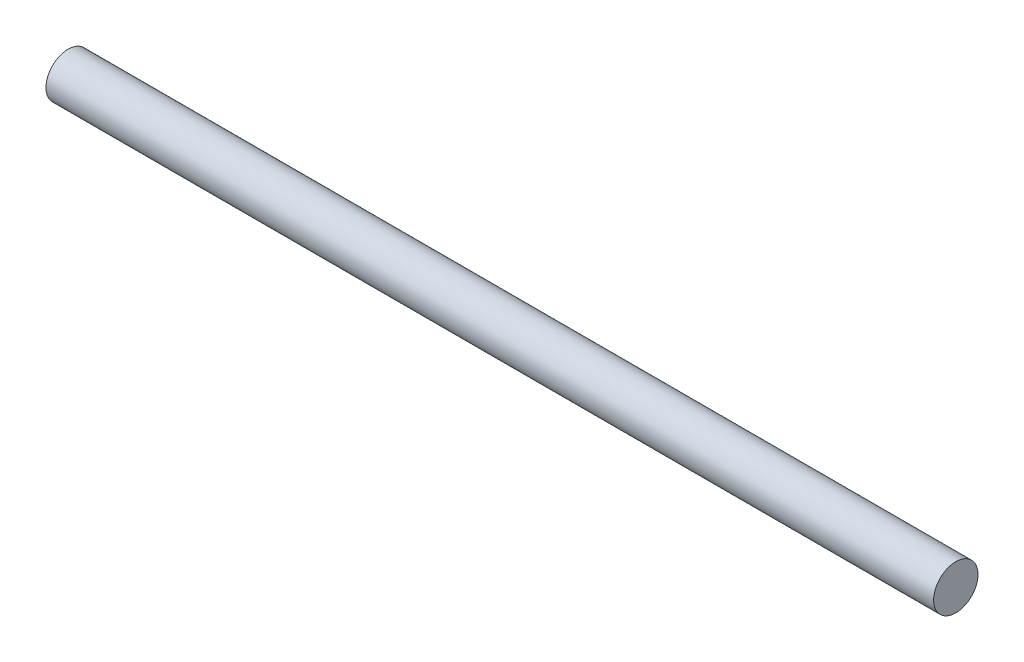
SolidWorks part; units mm, degrees
ref_plane "Front Plane" through (0, 0, 0) normal (0, 0, 1) x (1, 0, 0)
ref_plane "Top Plane" through (0, 0, 0) normal (0, 1, 0) x (1, 0, 0)
ref_plane "Right Plane" through (0, 0, 0) normal (1, 0, 0) x (0, 0, -1)
sketch "Sketch1" plane through (0, 0, 0) normal (1, 0, 0) x (0, 0, -1)
  circle A0 centre (0, 0) radius 6.35
  dimension "0.5" = 12.7
extrude "Boss-Extrude1" add sketch "Sketch1" along normal blind 254
